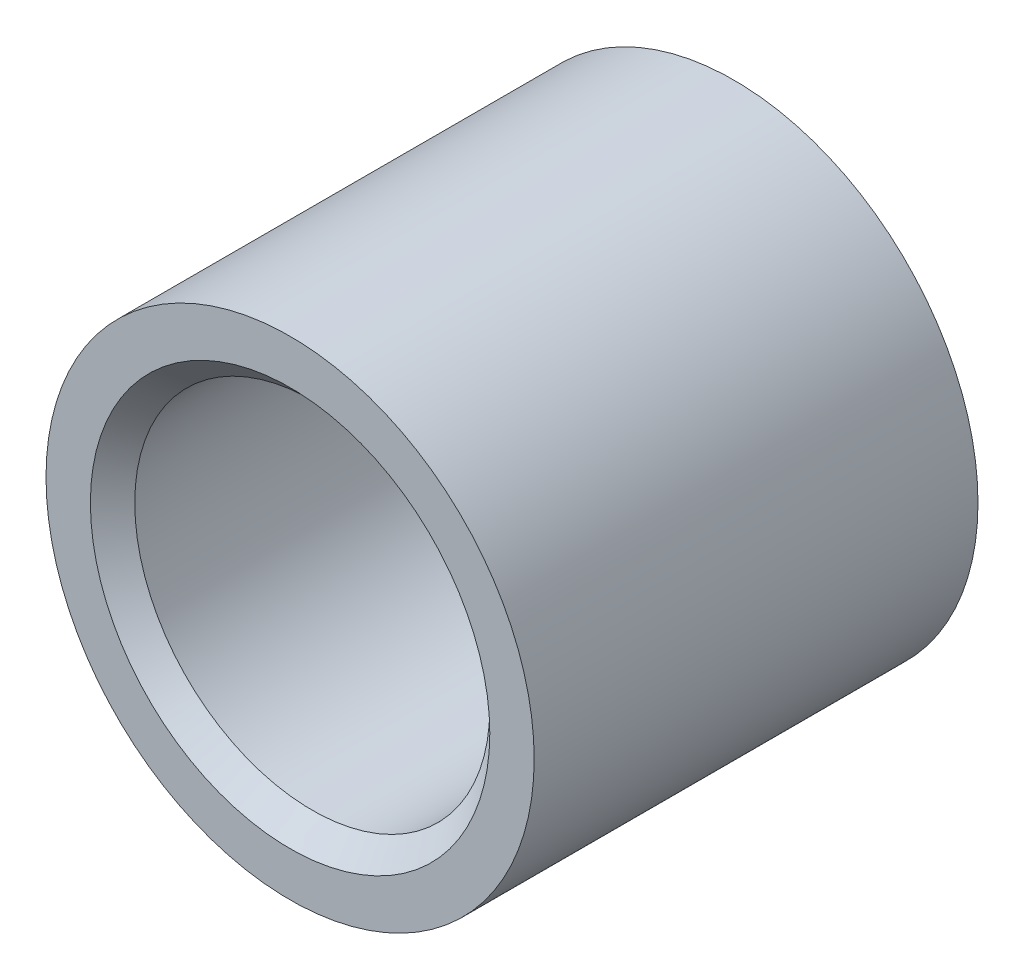
SolidWorks part; units mm, degrees
material "AISI 4130 Steel, normalized at 870C"
ref_plane "Front Plane" through (0, 0, 0) normal (0, 0, 1) x (1, 0, 0)
ref_plane "Top Plane" through (0, 0, 0) normal (0, 1, 0) x (1, 0, 0)
ref_plane "Right Plane" through (0, 0, 0) normal (1, 0, 0) x (0, 0, -1)
sketch "Sketch1" plane through (0, 0, 0) normal (0, 0, 1) x (1, 0, 0)
  circle A0 centre (0, 0) radius 10.16
  circle A1 centre (0, 0) radius 13.97
  dimension "D1" = 20.32
  dimension "D2" = 3.81
extrude "Boss-Extrude1" add sketch "Sketch1" along normal blind 25.4
chamfer "Chamfer1" distance 1.27 angle 45 2 edges at (10.16, 0, 0) (10.16, 0, 25.4)
